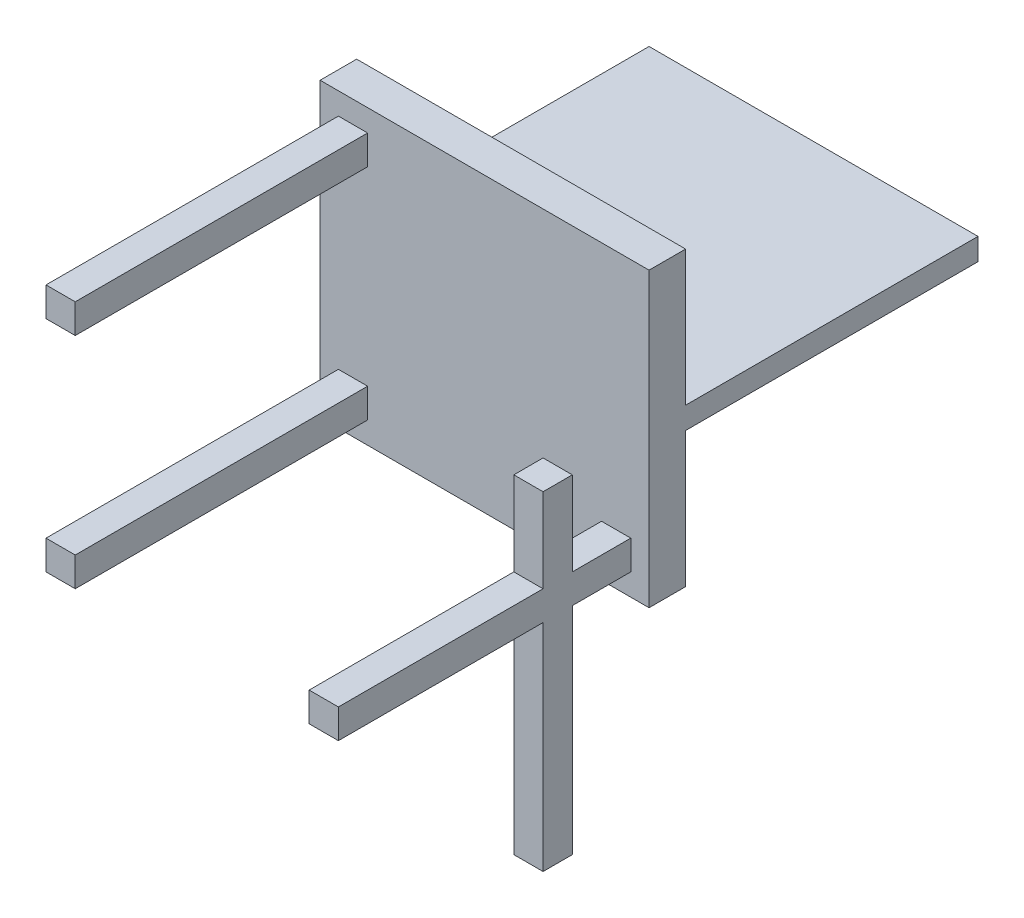
SolidWorks part; units mm, degrees
ref_plane "前视基准面" through (0, 0, 0) normal (0, 0, 1) x (1, 0, 0)
ref_plane "上视基准面" through (0, 0, 0) normal (0, 1, 0) x (1, 0, 0)
ref_plane "右视基准面" through (0, 0, 0) normal (1, 0, 0) x (0, 0, -1)
other "Configuration Table"
sketch "草图1" plane through (0, 0, 0) normal (0, 0, 1) x (1, 0, 0)
  line L1 (-225, -200) -> (225, -200)
  line L2 (-225, -200) -> (-225, 200)
  line L3 (-225, 200) -> (225, 200)
  line L4 (225, -200) -> (225, 200)
  line L5 (-225, -200) -> (225, 200) construction
  line L6 (-225, 200) -> (225, -200) construction
  point P0 (0, 0)
extrude "凸台-拉伸1" add sketch "草图1" along normal blind 50
sketch "草图2" plane through (0, 0, 0) normal (0, 0, -1) x (-1, 0, 0)
  line L0 (225, 200) -> (225, -200) construction
  line L1 (-225, -15) -> (225, -15)
  line L2 (-225, -15) -> (-225, 15)
  line L3 (-225, 15) -> (225, 15)
  line L4 (225, -15) -> (225, 15)
  line L5 (-225, -15) -> (225, 15) construction
  line L6 (-225, 15) -> (225, -15) construction
  point P0 (0, 0)
extrude "凸台-拉伸2" add sketch "草图2" along normal blind 400
sketch "草图3" plane through (0, -15, 0) normal (0, -1, 0) x (1, 0, 0)
  line L1 (160, 130) -> (200, 130)
  line L2 (160, 130) -> (160, 170)
  line L3 (160, 170) -> (200, 170)
  line L4 (200, 130) -> (200, 170)
  line L5 (160, 130) -> (200, 170) construction
  line L6 (160, 170) -> (200, 130) construction
  point P0 (180, 150)
extrude "凸台-拉伸3" add sketch "草图3" along normal blind 450
sketch "草图4" plane through (0, 0, 0) normal (0, 0, 1) x (1, 0, 0)
  line L1 (-200, 130) -> (-160, 130)
  line L2 (-200, 130) -> (-200, 170)
  line L3 (-200, 170) -> (-160, 170)
  line L4 (-160, 130) -> (-160, 170)
  line L5 (-200, 130) -> (-160, 170) construction
  line L6 (-200, 170) -> (-160, 130) construction
  point P0 (-180, 150)
extrude "凸台-拉伸4" add sketch "草图4" along normal blind 450
sketch "草图5" plane through (0, 0, 0) normal (0, 0, 1) x (1, 0, 0)
  line L1 (160, -170) -> (200, -170)
  line L2 (160, -170) -> (160, -130)
  line L3 (160, -130) -> (200, -130)
  line L4 (200, -170) -> (200, -130)
  line L5 (160, -170) -> (200, -130) construction
  line L6 (160, -130) -> (200, -170) construction
  point P0 (180, -150)
extrude "凸台-拉伸5" add sketch "草图5" along normal blind 450
sketch "草图6" plane through (0, 0, 0) normal (0, 0, 1) x (1, 0, 0)
  line L1 (-200, -170) -> (-160, -170)
  line L2 (-200, -170) -> (-200, -130)
  line L3 (-200, -130) -> (-160, -130)
  line L4 (-160, -170) -> (-160, -130)
  line L5 (-200, -170) -> (-160, -130) construction
  line L6 (-200, -130) -> (-160, -170) construction
  point P0 (-180, -150)
extrude "凸台-拉伸6" add sketch "草图6" along normal blind 450
